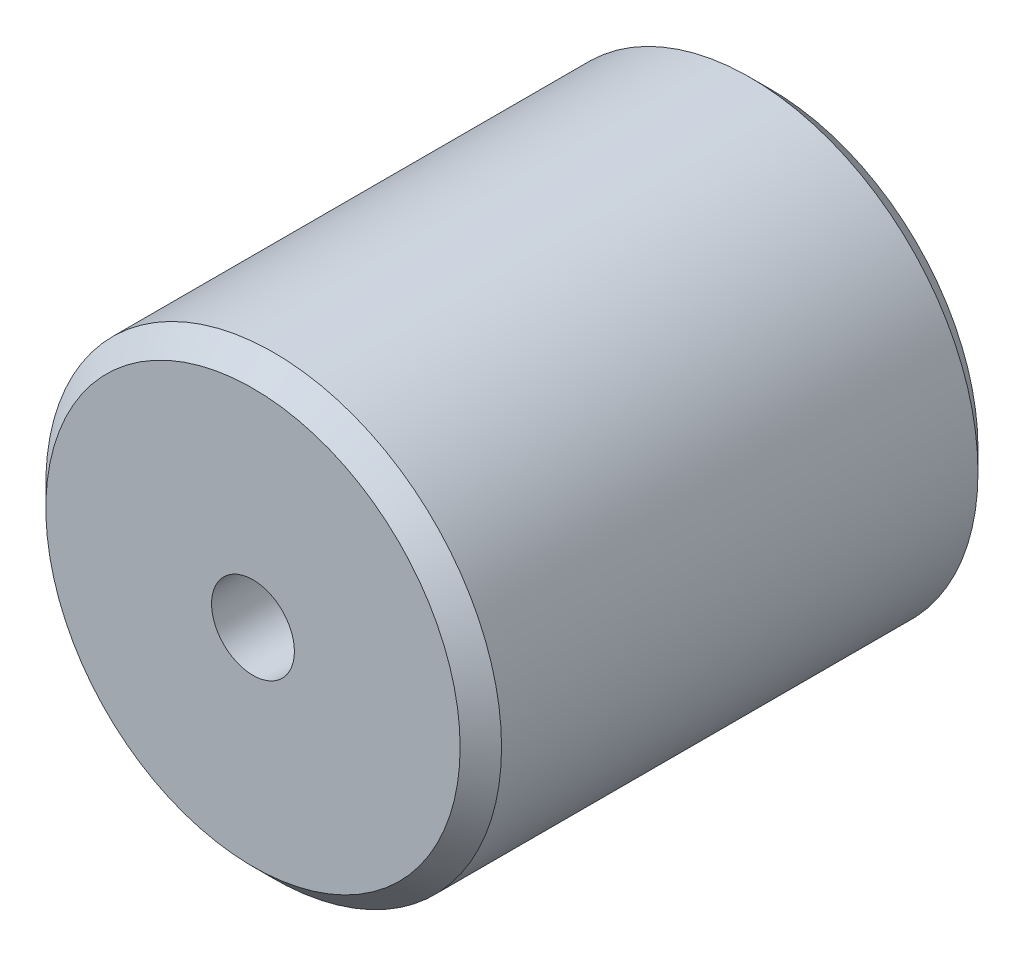
SolidWorks part; units mm, degrees
material "EPDM 60 Durometer"
ref_plane "xy" through (0, 0, 0) normal (0, 0, 1) x (1, 0, 0)
ref_plane "xz" through (0, 0, 0) normal (0, 1, 0) x (1, 0, 0)
ref_plane "yz" through (0, 0, 0) normal (1, 0, 0) x (0, 0, -1)
sketch "Skizze1" plane through (0, 0, 0) normal (0, 0, 1) x (1, 0, 0)
  circle A0 centre (0, 0) radius 11
  circle A1 centre (0, 0) radius 2
  dimension "D1" = 22
  dimension "D2" = 4
extrude "Aufsatz-Linear austragen1" add sketch "Skizze1" along normal blind 25
chamfer "Fase1" distance 1 angle 45 2 edges at (11, 0, 0) (11, 0, 25)
